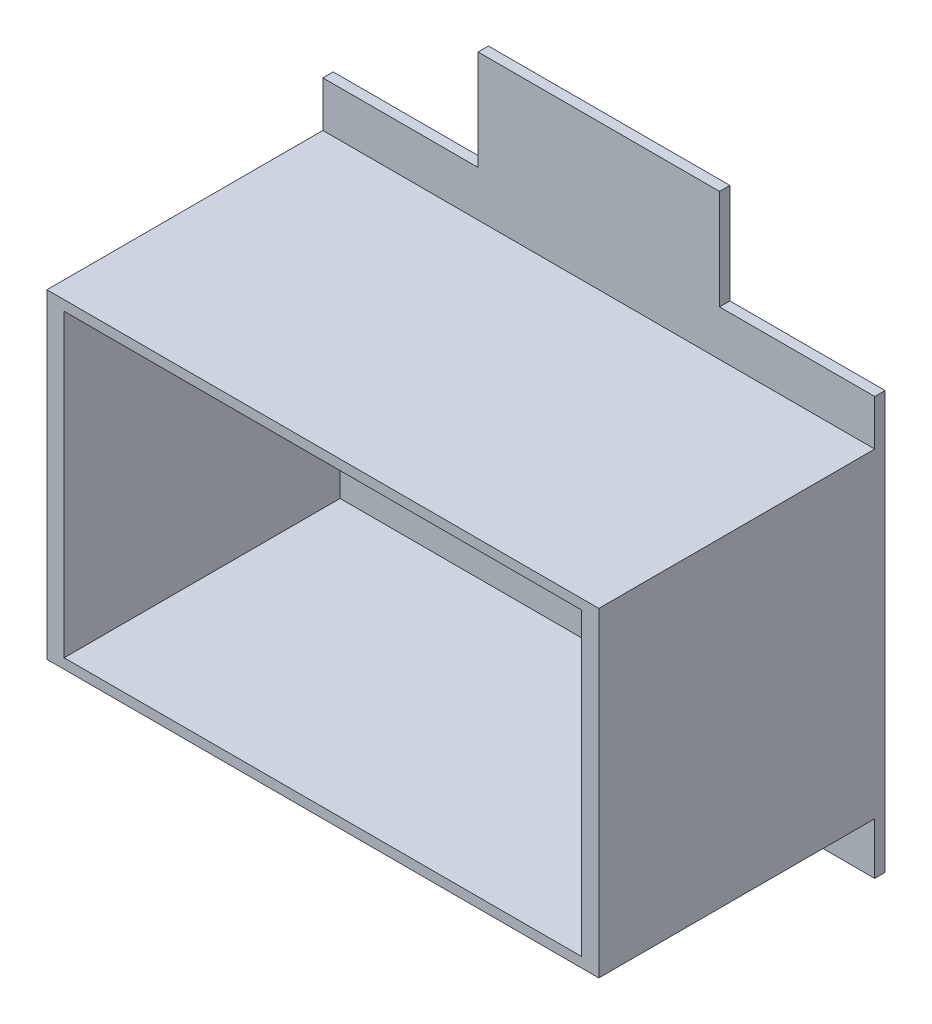
SolidWorks part; units mm, degrees
ref_plane "Front Plane" through (0, 0, 0) normal (0, 0, 1) x (1, 0, 0)
ref_plane "Top Plane" through (0, 0, 0) normal (0, 1, 0) x (1, 0, 0)
ref_plane "Right Plane" through (0, 0, 0) normal (1, 0, 0) x (0, 0, -1)
sketch "ｽｹｯﾁ1" plane through (0, 0, 0) normal (0, 0, 1) x (1, 0, 0)
  line L1 (-80, 75) -> (80, 75)
  line L2 (-80, 75) -> (-80, -75)
  line L3 (-80, -75) -> (80, -75)
  line L4 (80, 75) -> (80, -75)
  line L5 (-80, 75) -> (80, -75) construction
  line L6 (-80, -75) -> (80, 75) construction
  point P0 (0, 0)
  dimension "D1" = 160
  dimension "D2" = 150
extrude "ﾎﾞｽ - 押し出し1" add sketch "ｽｹｯﾁ1" along normal blind 3
sketch "ｽｹｯﾁ2" plane through (0, 0, 3) normal (0, 0, 1) x (1, 0, 0)
  line L0 (-80, -75) -> (80, -75) construction
  line L1 (-80, 32.8) -> (80, 32.8)
  line L2 (-80, 32.8) -> (-80, -60)
  line L3 (-80, -60) -> (80, -60)
  line L4 (80, 32.8) -> (80, -60)
  line L5 (-80, 32.8) -> (80, -60) construction
  line L6 (-80, -60) -> (80, 32.8) construction
  line L7 (-75, 29.9) -> (75, 29.9)
  line L8 (-75, 29.9) -> (-75, -57.1)
  line L9 (-75, -57.1) -> (75, -57.1)
  line L10 (75, 29.9) -> (75, -57.1)
  line L11 (-75, 29.9) -> (75, -57.1) construction
  line L12 (-75, -57.1) -> (75, 29.9) construction
  line L14 (0, 0) -> (0, -60) construction
  point P5 (0, 0)
  point P7 (0, -57.1)
  dimension "D1" = 160
  dimension "D2" = 150
  dimension "D3" = 87
  dimension "D4" = 15
extrude "ﾎﾞｽ - 押し出し2" add sketch "ｽｹｯﾁ2" along normal blind 80
sketch "ｽｹｯﾁ4" plane through (0, 0, 3) normal (0, 0, 1) x (1, 0, 0)
  line L0 (0, -55) -> (0, 55) construction
  line L1 (-80, 75) -> (-35, 75)
  line L2 (-80, 75) -> (-80, 46)
  line L3 (-80, 46) -> (-35, 46)
  line L4 (-35, 75) -> (-35, 46)
  line L5 (80, 75) -> (35, 75)
  line L6 (80, 75) -> (80, 46)
  line L7 (80, 46) -> (35, 46)
  line L8 (35, 75) -> (35, 46)
  dimension "D1" = 45
  dimension "D2" = 29
extrude "ｶｯﾄ - 押し出し2" cut sketch "ｽｹｯﾁ4" against normal blind 3
